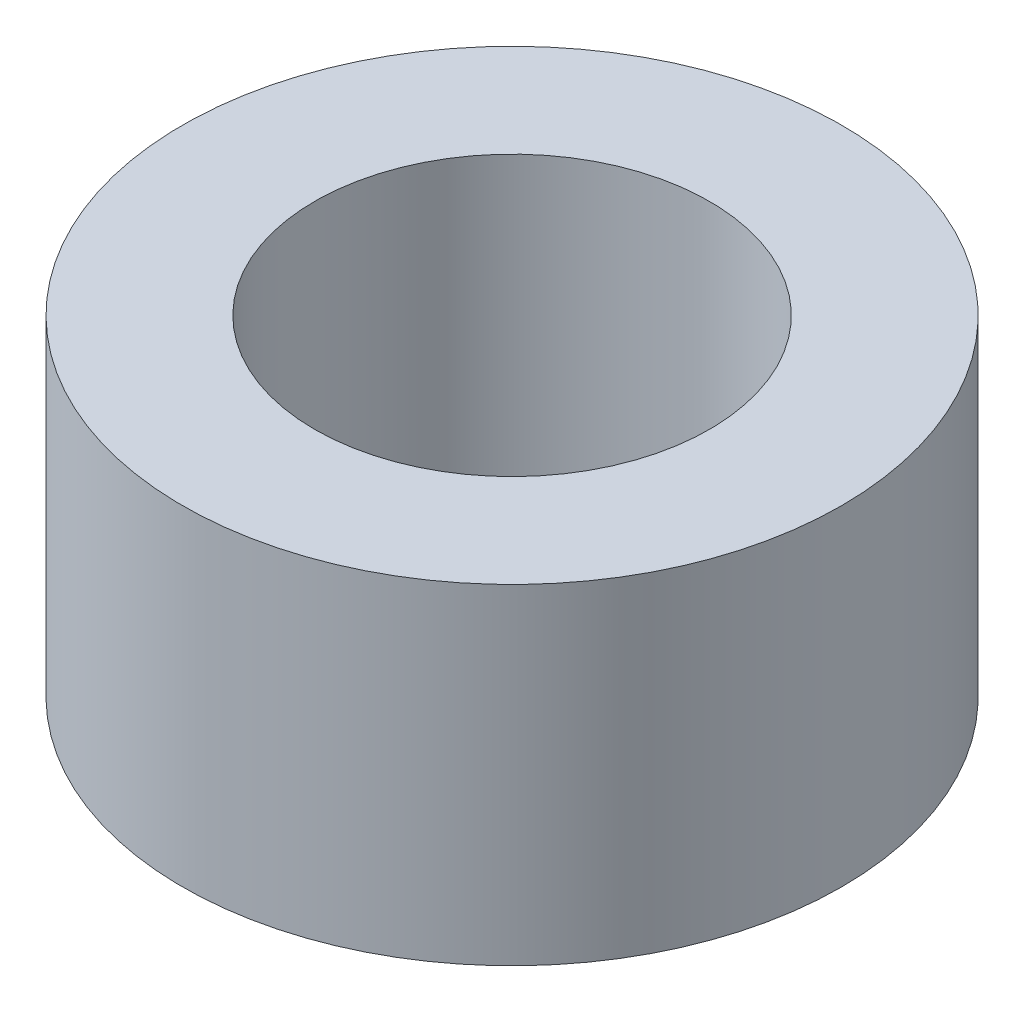
SolidWorks part; units mm, degrees
ref_plane "Front Plane" through (0, 0, 0) normal (0, 0, 1) x (1, 0, 0)
ref_plane "Top Plane" through (0, 0, 0) normal (0, 1, 0) x (1, 0, 0)
ref_plane "Right Plane" through (0, 0, 0) normal (1, 0, 0) x (0, 0, -1)
sketch "Sketch1" plane through (0, 0, 0) normal (0, 1, 0) x (1, 0, 0)
  circle A0 centre (0, 0) radius 1.495
  dimension "D1" = 2.99
extrude "Extrude-Thin1" add sketch "Sketch1" along normal blind 2.5 thin
